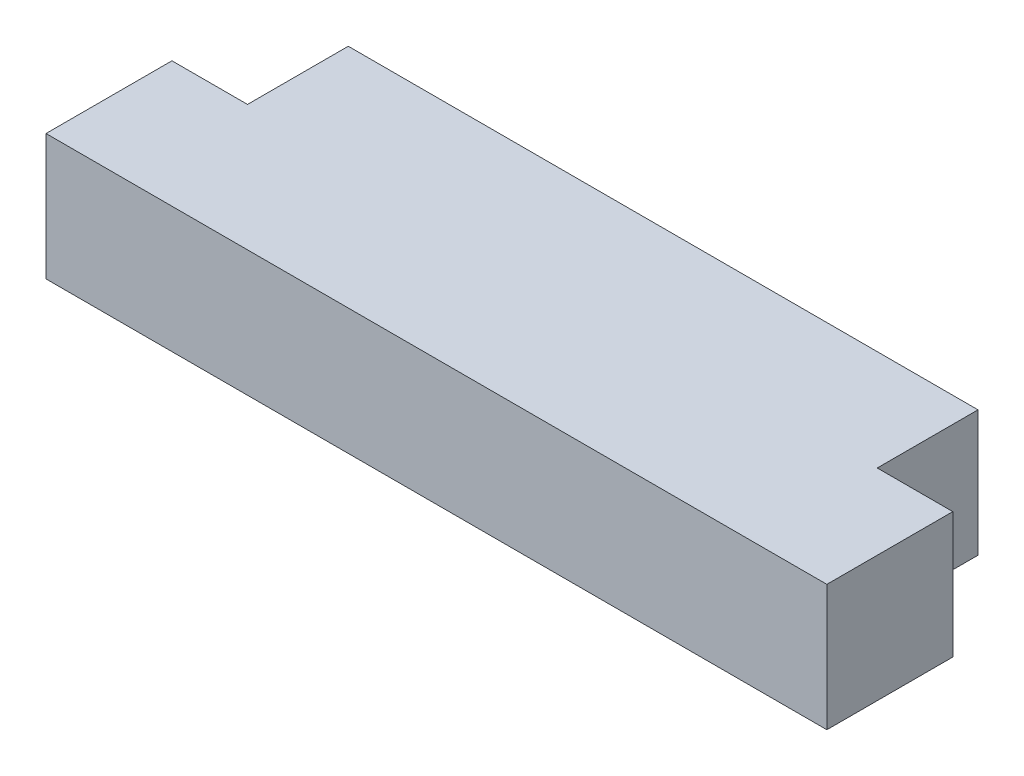
SolidWorks part; units mm, degrees
ref_plane "Front Plane" through (0, 0, 0) normal (0, 0, 1) x (1, 0, 0)
ref_plane "Top Plane" through (0, 0, 0) normal (0, 1, 0) x (1, 0, 0)
ref_plane "Right Plane" through (0, 0, 0) normal (1, 0, 0) x (0, 0, -1)
sketch "Sketch1" plane through (0, 0, 0) normal (0, 1, 0) x (1, 0, 0)
  line L0 (0, 0) -> (0, 5)
  line L1 (0, 5) -> (3, 5)
  line L2 (3, 5) -> (3, 9)
  line L3 (3, 9) -> (28, 9)
  line L4 (28, 9) -> (28, 5)
  line L5 (28, 5) -> (31, 5)
  line L6 (31, 5) -> (31, 0)
  line L7 (31, 0) -> (0, 0)
  dimension "D1" = 5
  dimension "D2" = 4
  dimension "D3" = 3
  dimension "D4" = 31
extrude "Boss-Extrude1" add sketch "Sketch1" along normal blind 5
